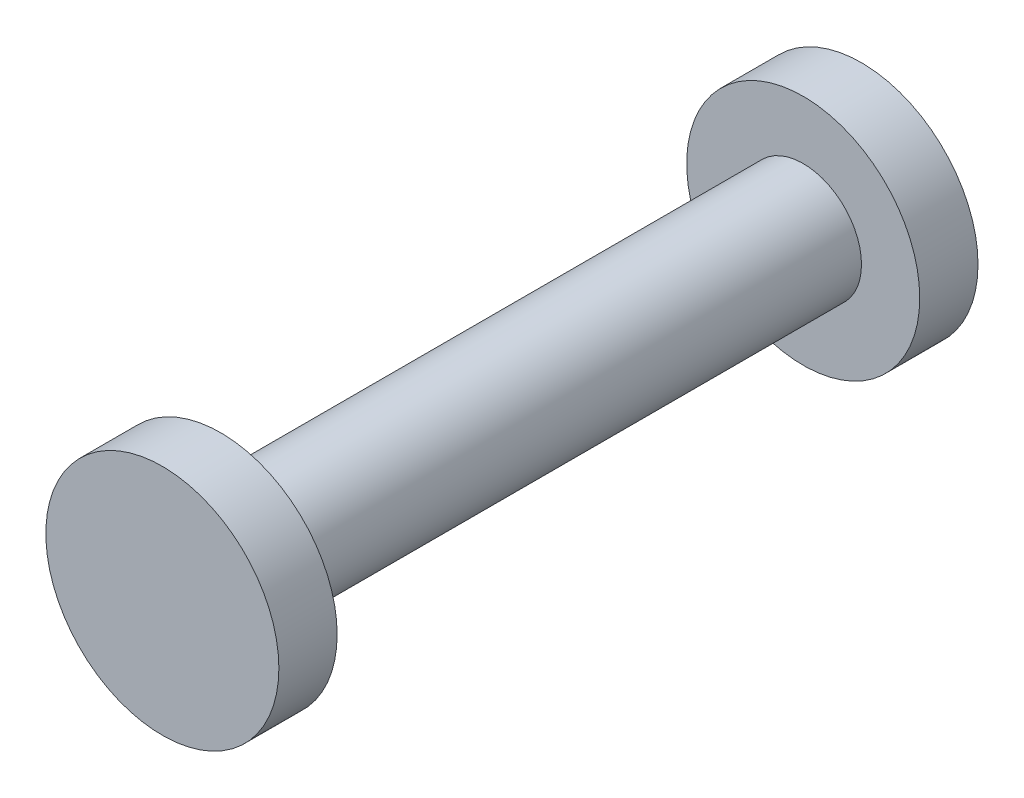
SolidWorks part; units mm, degrees
ref_plane "Front Plane" through (0, 0, 0) normal (0, 0, 1) x (1, 0, 0)
ref_plane "Top Plane" through (0, 0, 0) normal (0, 1, 0) x (1, 0, 0)
ref_plane "Right Plane" through (0, 0, 0) normal (1, 0, 0) x (0, 0, -1)
sketch "Sketch1" plane through (0, 0, 0) normal (0, 0, 1) x (1, 0, 0)
  circle A0 centre (0, 0) radius 5
  dimension "D1" = 10
extrude "Boss-Extrude1" add sketch "Sketch1" along normal mid plane 50
sketch "Sketch2" plane through (0, 0, 25) normal (0, 0, 1) x (1, 0, 0)
  circle A0 centre (0, 0) radius 10
  dimension "D1" = 20
extrude "Boss-Extrude2" add sketch "Sketch2" along normal blind 5
mirror "Mirror1" about plane through (0, 0, 0) normal (0, 0, 1) of "Boss-Extrude2"
